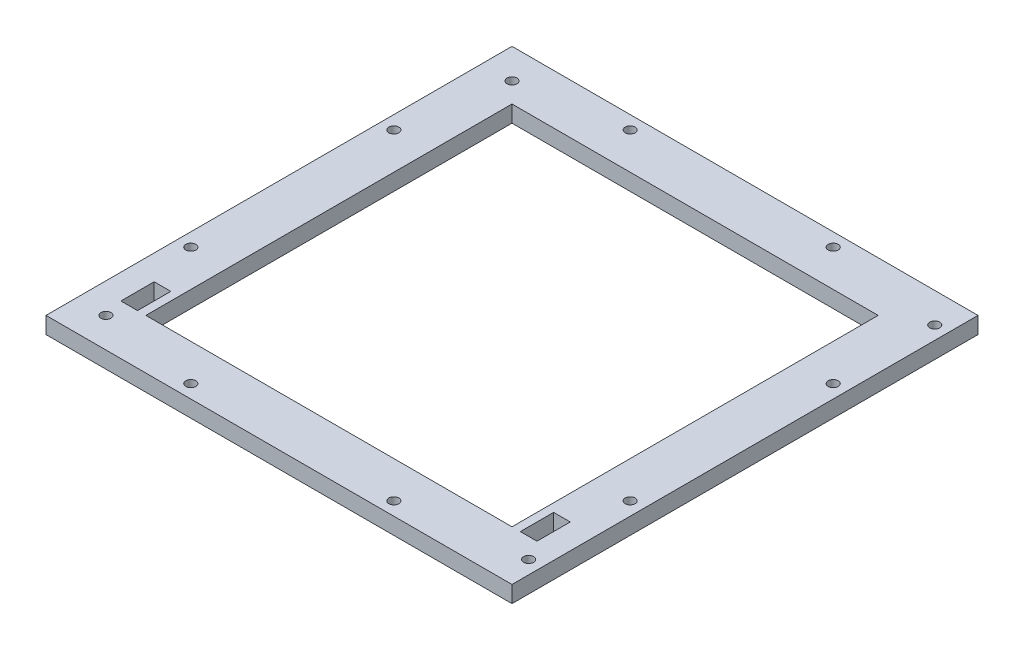
SolidWorks part; units mm, degrees
ref_plane "Alzado" through (0, 0, 0) normal (0, 0, 1) x (1, 0, 0)
ref_plane "Planta" through (0, 0, 0) normal (0, 1, 0) x (1, 0, 0)
ref_plane "Vista lateral" through (0, 0, 0) normal (1, 0, 0) x (0, 0, -1)
sketch "Croquis1" plane through (0, 0, 0) normal (0, 1, 0) x (1, 0, 0)
  line L0 (0, 0) -> (-62.5, 0) construction
  line L1 (-62.5, 0) -> (-62.5, 55) construction
  line L2 (-62.5, 55) -> (-55, 62.5) construction
  line L3 (-55, 62.5) -> (0, 62.5) construction
  line L4 (0, 62.5) -> (0, 0) construction
  line L5 (62.5, 55) -> (62.5, 0) construction
  line L6 (55, 62.5) -> (62.5, 55) construction
  line L7 (0, 62.5) -> (55, 62.5) construction
  line L8 (55, -62.5) -> (0, -62.5) construction
  line L9 (62.5, -55) -> (55, -62.5) construction
  line L10 (62.5, 0) -> (62.5, -55) construction
  line L11 (-62.5, -55) -> (-62.5, 0) construction
  line L12 (-55, -62.5) -> (-62.5, -55) construction
  line L13 (0, -62.5) -> (-55, -62.5) construction
  line L14 (0, -70) -> (0, -62.5) construction
  line L15 (0, 0) -> (-61, 0) construction
  line L16 (0, 0) -> (0, 61) construction
  line L17 (0, 61) -> (-61, 61) construction
  line L18 (-61, 0) -> (-61, 61) construction
  line L19 (0, 0) -> (-61, 0) construction
  line L20 (0, 0) -> (0, -61) construction
  line L21 (0, -61) -> (-61, -61) construction
  line L22 (-61, 0) -> (-61, -61) construction
  line L23 (0, 0) -> (66, 0) construction
  line L24 (0, 0) -> (0, -61) construction
  line L25 (0, -61) -> (66, -61) construction
  line L26 (66, 0) -> (66, -61) construction
  line L27 (0, 0) -> (66, 0) construction
  line L28 (0, 0) -> (0, 61) construction
  line L29 (0, 61) -> (66, 61) construction
  line L30 (66, 0) -> (66, 61) construction
  line L35 (25, -25) -> (-25, 25) construction
  line L36 (25, 25) -> (-25, -25) construction
  line L37 (70, -70) -> (-70, -70)
  line L38 (70, -70) -> (70, 70)
  line L39 (70, 70) -> (-70, 70)
  line L40 (-70, -70) -> (-70, 70)
  line L41 (70, -70) -> (-70, 70) construction
  line L42 (70, 70) -> (-70, -70) construction
  line L43 (-30.5, -66) -> (30.5, -66) construction
  line L53 (-55, 55) -> (55, 55)
  line L54 (-55, 55) -> (-55, -55)
  line L55 (-55, -55) -> (55, -55)
  line L56 (55, 55) -> (55, -55)
  line L57 (-55, 55) -> (55, -55) construction
  line L58 (-55, -55) -> (55, 55) construction
  circle A0 centre (-61, 61) radius 1.5
  circle A1 centre (66, 61) radius 1.5
  circle A2 centre (66, -61) radius 1.5
  circle A3 centre (-61, -61) radius 1.5
  circle A4 centre (66, 30.5) radius 1.5
  circle A5 centre (66, -30.5) radius 1.5
  circle A6 centre (-30.5, -66) radius 1.5
  circle A7 centre (30.5, -66) radius 1.5
  circle A8 centre (-30.5, 66) radius 1.5
  circle A9 centre (30.5, 66) radius 1.5
  circle A10 centre (-66, 30.5) radius 1.5
  circle A11 centre (-66, -30.5) radius 1.5
  point P48 (0, -66)
  dimension "D6" = 3
  dimension "D9" = 4
  dimension "D10" = 3
  dimension "D1" = 55
  dimension "D2" = 62.5
  dimension "D4" = 61
  dimension "D5" = 66
  dimension "D7" = 110
  dimension "D8" = 140
  dimension "D11" = 61
  dimension "D3" = 4
extrude "Saliente-Extruir1" add sketch "Croquis1" along normal blind 5
sketch "Croquis2" plane through (0, 5, 0) normal (0, 1, 0) x (1, 0, 0)
  line L0 (57.5, -50) -> (55.5, -50) construction
  line L1 (57.5, -55) -> (62.5, -55)
  line L2 (57.5, -55) -> (57.5, -45)
  line L3 (57.5, -45) -> (62.5, -45)
  line L4 (62.5, -55) -> (62.5, -45)
  line L6 (70, -70) -> (70, 70) construction
  line L7 (0, 0) -> (0, 55) construction
  line L8 (55, 55) -> (-55, 55) construction
  line L9 (-57.5, -45) -> (-62.5, -45)
  line L10 (-62.5, -55) -> (-62.5, -45)
  line L11 (-57.5, -55) -> (-62.5, -55)
  line L12 (-57.5, -55) -> (-57.5, -45)
  line L13 (-55, -55) -> (55, -55) construction
  dimension "D1" = 2
  dimension "D2" = 7.5
  dimension "D3" = 10
  dimension "D4" = 5
extrude "Cortar-Extruir1" cut sketch "Croquis2" against normal blind 5
